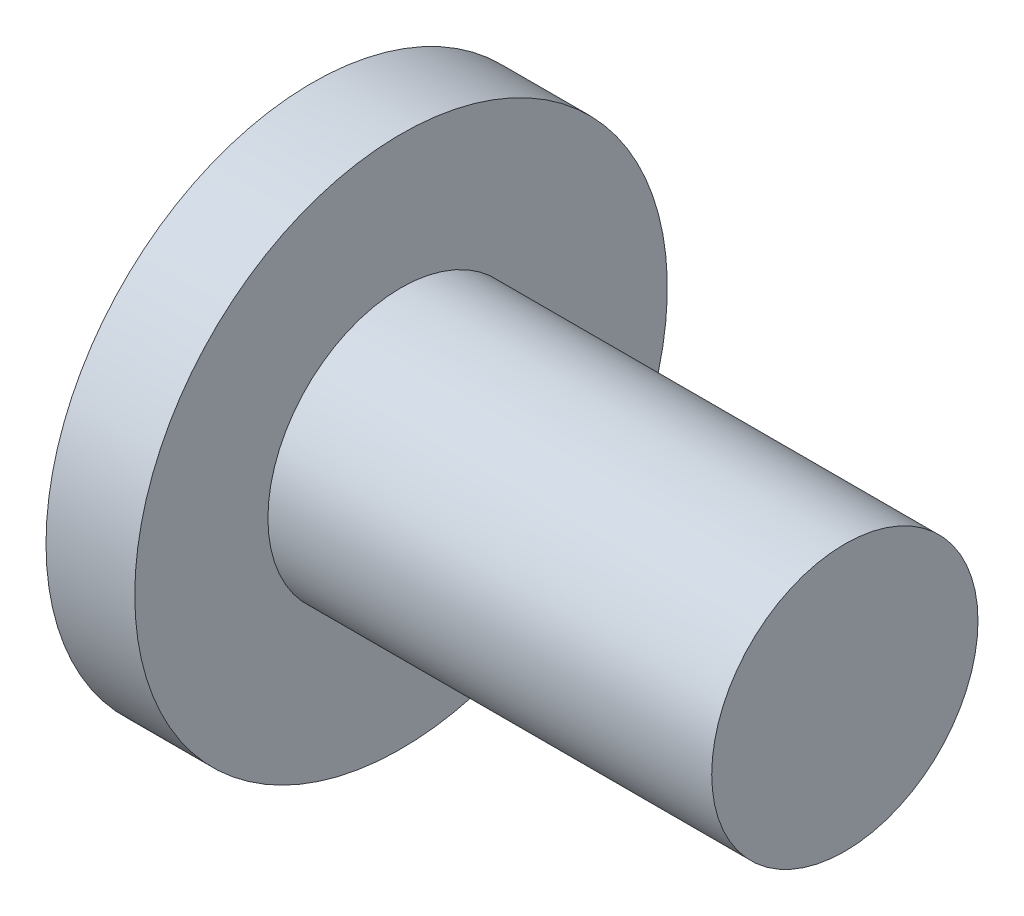
SolidWorks part; units mm, degrees
material "AISI 4340 Çelik, tavlı"
ref_plane "Ön Düzlem" through (0, 0, 0) normal (0, 0, 1) x (1, 0, 0)
ref_plane "Üst Düzlem" through (0, 0, 0) normal (0, 1, 0) x (1, 0, 0)
ref_plane "Sağ Düzlem" through (0, 0, 0) normal (1, 0, 0) x (0, 0, -1)
sketch "Çizim1" plane through (0, 0, 0) normal (0, 0, 1) x (1, 0, 0)
  line L0 (0, 0) -> (0, 3)
  line L1 (0, 3) -> (-10, 3)
  line L2 (-10, 3) -> (-10, 6)
  line L3 (-10, 6) -> (-12, 6)
  line L4 (-12, 6) -> (-12, 0)
  line L5 (-12, 0) -> (0, 0)
  dimension "D1" = 3
  dimension "D2" = 10
  dimension "D3" = 2
  dimension "D4" = 6
revolve "Döndür1" add sketch "Çizim1" angle 360 about L5
